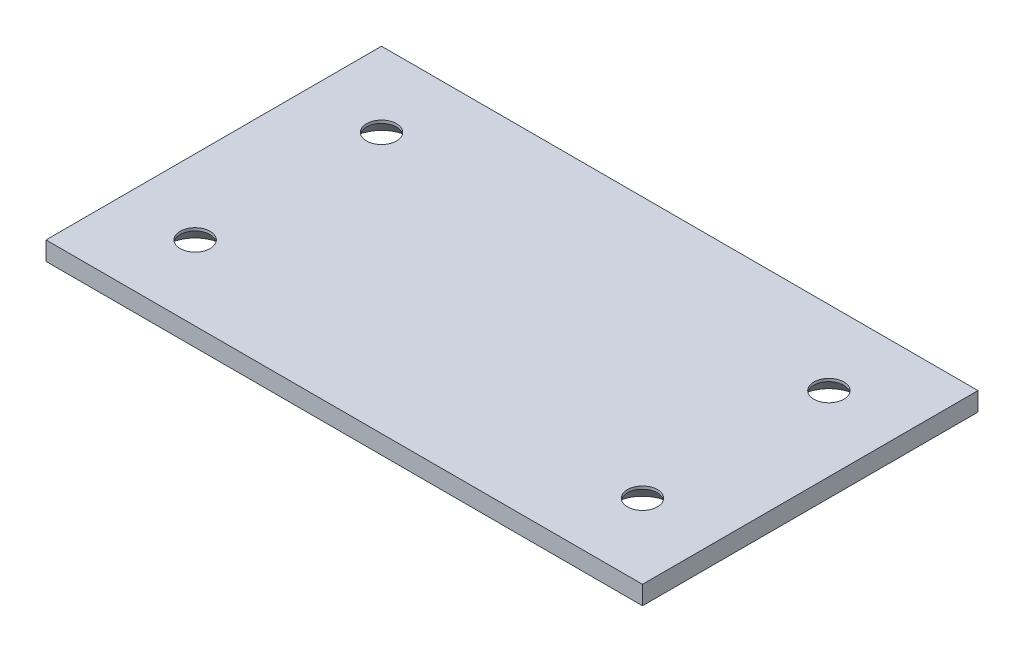
SolidWorks part; units mm, degrees
ref_plane "Front Plane" through (0, 0, 0) normal (0, 0, 1) x (1, 0, 0)
ref_plane "Top Plane" through (0, 0, 0) normal (0, 1, 0) x (1, 0, 0)
ref_plane "Right Plane" through (0, 0, 0) normal (1, 0, 0) x (0, 0, -1)
sketch "Sketch1" plane through (0, 0, 0) normal (0, 1, 0) x (1, 0, 0)
  line L1 (-50.8, -28.575) -> (50.8, -28.575)
  line L2 (-50.8, -28.575) -> (-50.8, 28.575)
  line L3 (-50.8, 28.575) -> (50.8, 28.575)
  line L4 (50.8, -28.575) -> (50.8, 28.575)
  line L5 (-50.8, -28.575) -> (50.8, 28.575) construction
  line L6 (-50.8, 28.575) -> (50.8, -28.575) construction
  point P0 (0, 0)
  dimension "D1" = 57.15
  dimension "D2" = 101.6
extrude "Boss-Extrude1" add sketch "Sketch1" along normal blind 3.175
sketch "Sketch2" plane through (0, 3.175, 0) normal (0, 1, 0) x (1, 0, 0)
  line L0 (-55, 0) -> (55, 0) construction
  line L1 (-17.78, 17.78) -> (17.78, 17.78) construction
  line L2 (17.78, 17.78) -> (17.78, -17.78) construction
  line L3 (17.78, -17.78) -> (-17.78, -17.78) construction
  line L4 (-17.78, -17.78) -> (-17.78, 17.78) construction
  line L6 (-50.8, 28.575) -> (-50.8, -28.575) construction
  circle A0 centre (0, 0) radius 20.701
  point P4 (17.78, 17.78)
  point P5 (-17.78, 17.78)
  point P6 (-17.78, -17.78)
  point P7 (17.78, -17.78)
  point P9 (0, 17.78)
  point P11 (-17.78, 0)
  dimension "D1" = 41.402
  dimension "D2" = 35.56
  dimension "D3" = 35.56
  dimension "D4" = 50.8
hole_wizard "1/8 (0.125) Diameter Hole1" [suppressed] positions "Sketch3" profile "Sketch5" hole size "1/8" standard "ANSI Inch"
sketch "Sketch3" plane through (0, 3.175, 0) normal (0, 1, 0) x (1, 0, 0)
  point P0 (-17.78, 17.78)
  point P3 (17.78, 17.78)
  point P6 (17.78, -17.78)
  point P9 (-17.78, -17.78)
sketch "Sketch5" plane through (-17.78, 3.175, -17.78) normal (1, 0, 0) x (0, 0, 1)
  line L0 (0, 0) -> (0, 3.175)
  line L1 (0, 3.175) -> (1.5875, 3.175)
  line L2 (1.5875, 3.175) -> (1.5875, 0)
  line L5 (1.5875, 0) -> (0, 0)
  line L11 (0, -6.35) -> (0, 107.95) construction
  dimension "Thru Hole Dia." = 3.175
  dimension "Thru Hole Depth" = 3.175
extrude "Cut-Extrude1" [suppressed] cut sketch "Sketch2" against normal through all contours A0
sketch "Sketch6" plane through (0, 0, 0) normal (0, 1, 0) x (1, 0, 0)
  line L0 (50.8, 28.575) -> (-50.8, 28.575) construction
  line L1 (-50.8, -28.575) -> (50.8, -28.575) construction
  line L2 (-50.8, 28.575) -> (-50.8, -28.575) construction
  line L5 (50.8, -28.575) -> (50.8, 28.575) construction
  point P0 (-38.1, 15.875)
  point P1 (-38.1, -15.875)
  point P8 (38.1, -15.875)
  point P9 (38.1, 15.875)
  dimension "D1" = 12.7
  dimension "D2" = 12.7
  dimension "D3" = 12.7
  dimension "D4" = 12.7
hole_wizard "CSK for #10 Flat Head Machine Screw1" positions "Sketch9" profile "Sketch10" countersink size "#10" standard "ANSI Inch" end condition through all
sketch "Sketch9" plane through (0, 0, 0) normal (0, -1, 0) x (-1, 0, 0)
  point P0 (38.1, -15.875)
  point P3 (38.1, 15.875)
  point P6 (-38.1, -15.875)
  point P9 (-38.1, 15.875)
sketch "Sketch10" plane through (-38.1, 0, 15.875) normal (1, 0, 0) x (0, 0, -1)
  line L0 (0, 0) -> (0, 3.175)
  line L1 (0, 3.175) -> (2.5527, 3.175)
  line L2 (2.5527, 3.175) -> (2.5527, 2.6882)
  line L3 (2.5527, 2.6882) -> (4.8895, 0)
  line L5 (4.8895, 0) -> (0, 0)
  line L6 (-2.5527, 2.6882) -> (-4.8895, 0) construction
  line L11 (0, -6.35) -> (0, 107.95) construction
  dimension "Thru Hole Dia." = 5.1054
  dimension "Thru Hole Depth" = 3.175
  dimension "Near C'Sink Dia." = 9.779
  dimension "Near C'Sink Angle" = 82
